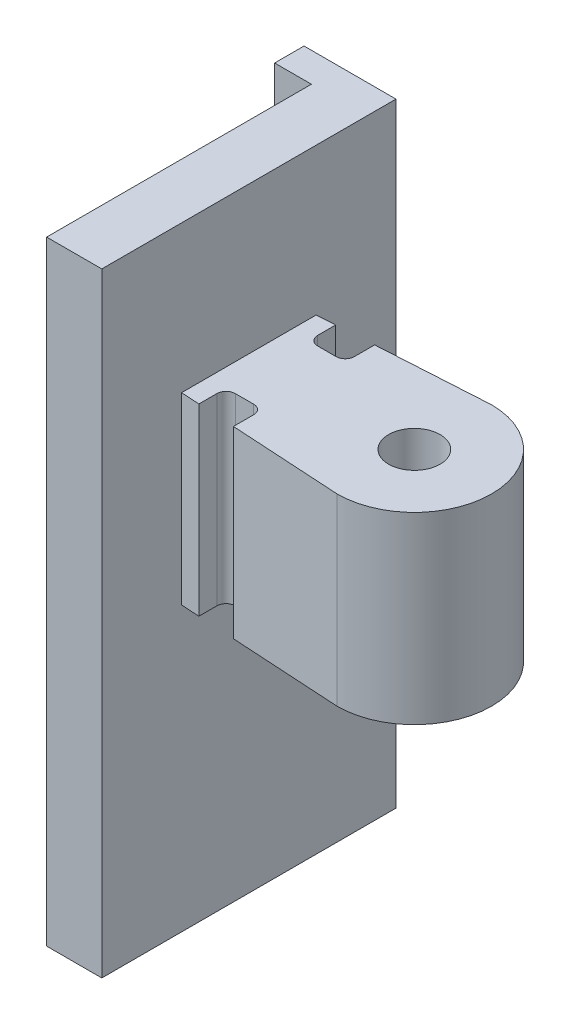
SolidWorks part; units mm, degrees
ref_plane "Front Plane" through (0, 0, 0) normal (0, 0, 1) x (1, 0, 0)
ref_plane "Top Plane" through (0, 0, 0) normal (0, 1, 0) x (1, 0, 0)
ref_plane "Right Plane" through (0, 0, 0) normal (1, 0, 0) x (0, 0, -1)
sketch "Sketch3" plane through (0, 0, 0) normal (0, 1, 0) x (1, 0, 0)
  line L0 (-5, 0.75) -> (0, 1.05) construction
  line L3 (0, -1.05) -> (-5, -0.75) construction
  line L4 (-2.5, 0.9) -> (-2, 0.93)
  line L6 (-4.25, 0) -> (-5.75, 0) construction
  line L7 (-2, 0.93) -> (-2, 0.56)
  line L8 (-2.5, 0.9) -> (-5, 0.9) construction
  line L9 (-2.5, 0.9) -> (-2.5, -0.9)
  line L10 (-2.5, -0.9) -> (-5, -0.9) construction
  line L11 (-5, 0.9) -> (-5, -0.9) construction
  line L12 (-2, 0.96) -> (-1.5, 0.96) construction
  line L13 (-2, 0.96) -> (-2, 0.56) construction
  line L14 (-2, 0.56) -> (-1.5, 0.56)
  line L15 (-1.5, 0.96) -> (-1.5, 0.56)
  line L16 (-1.5, -0.56) -> (-2, -0.56)
  line L17 (-1.5, -0.56) -> (-1.5, -0.96)
  line L18 (-1.5, -0.96) -> (-2, -0.96) construction
  line L19 (-2, -0.56) -> (-2, -0.96) construction
  line L21 (-2.5, -0.9) -> (-2, -0.93)
  line L22 (-2, -0.93) -> (-2, -0.56)
  line L23 (-1.5, 0.96) -> (0, 1.05)
  line L24 (0, -1.05) -> (-1.5, -0.96)
  circle A2 centre (0, 0) radius 0.6 construction
  circle A3 centre (0, 0) radius 0.4 construction
  circle A4 centre (-5, 0) radius 0.35 construction
  circle A5 centre (0, 0) radius 1.05 construction
  circle A6 centre (-5, 0) radius 0.75 construction
  arc A7 (-5, 0.9) -> (-5, -0.9) centre (-5, 0) ccw construction
  arc A8 (0, 1.05) -> (0, -1.05) centre (0, 0) cw
  point P4 (-2, -0.93)
  point P15 (-5, 0)
  point P16 (-2, 0.93)
  point P22 (-5, 0)
  dimension "D2" = 1.2
  dimension "D3" = 0.8
  dimension "D4" = 0.7
  dimension "D6" = 5
  dimension "D1" = 1.5
  dimension "D5" = 2.1
  dimension "D7" = 0.4
  dimension "D9" = 2.5
  dimension "D10" = 1.8
  dimension "D11" = 2.5
  dimension "D12" = 0.5
  dimension "D14" = 1.5
extrude "Boss-Extrude1" add sketch "Sketch3" along normal blind 2.5 contours L21 L22 L16 L17 L24 A8 L23 L15 L14 L7 L4 L9
sketch "Sketch4" plane through (0, 2.5, 0) normal (0, 1, 0) x (1, 0, 0)
  circle A0 centre (0, 0) radius 0.35
  point P9 (0, 0)
  dimension "D1" = 0.7
extrude "Through Holes" cut sketch "Sketch4" against normal through all contours A0
fillet "Fillet1" radius 0.125 4 edges at (-2, 1.25, 0.56) (-1.5, 1.25, 0.56) (-1.5, 1.25, -0.56) (-2, 1.25, -0.56)
sketch "Sketch5" plane through (0, 0, 0) normal (0, 1, 0) x (1, 0, 0)
  line L0 (-2.25, 0) -> (1.75, 0) construction
  line L1 (-2.25, -2) -> (1.75, -2)
  line L2 (-2.25, -2) -> (-2.25, 2)
  line L3 (-2.25, 2) -> (1.75, 2)
  line L4 (1.75, -2) -> (1.75, 2)
  line L5 (-2.25, -2) -> (1.75, 2) construction
  line L6 (-2.25, 2) -> (1.75, -2) construction
  circle A1 centre (0, 0) radius 0.125
  point P1 (-0.25, 0)
  dimension "D2" = 0.25
  dimension "D1" = 1.75
  dimension "D3" = 4
sketch "Sketch11" plane through (-2.5, 0, 0) normal (-1, 0, 0) x (0, 0, 1)
  line L0 (0, 2.5) -> (0, 4.5) construction
  line L1 (-2, 4.5) -> (2, 4.5)
  line L2 (-2, 4.5) -> (-2, -3.85)
  line L3 (-2, -3.85) -> (2, -3.85)
  line L4 (2, 4.5) -> (2, -3.85)
  line L5 (-0.9, 2.5) -> (0.9, 2.5) construction
  dimension "D1" = 4
  dimension "D2" = 8.35
  dimension "D3" = 2
extrude "Boss-Extrude4" add sketch "Sketch11" along normal blind 0.5 and the other way blind 0.25
sketch "Sketch12" plane through (-3, 0, 0) normal (-1, 0, 0) x (0, 0, 1)
  line L0 (-2, 4.5) -> (-1.6, 4.5)
  line L1 (2, 4.5) -> (-2, 4.5) construction
  line L2 (-1.6, 4.5) -> (-1.6, -3.85)
  line L3 (-2, -3.85) -> (2, -3.85) construction
  line L4 (-1.6, -3.85) -> (-2, -3.85)
  line L5 (-2, -3.85) -> (-2, 4.5)
  dimension "D1" = 0.4
extrude "Boss-Extrude5" add sketch "Sketch12" along normal blind 0.5
